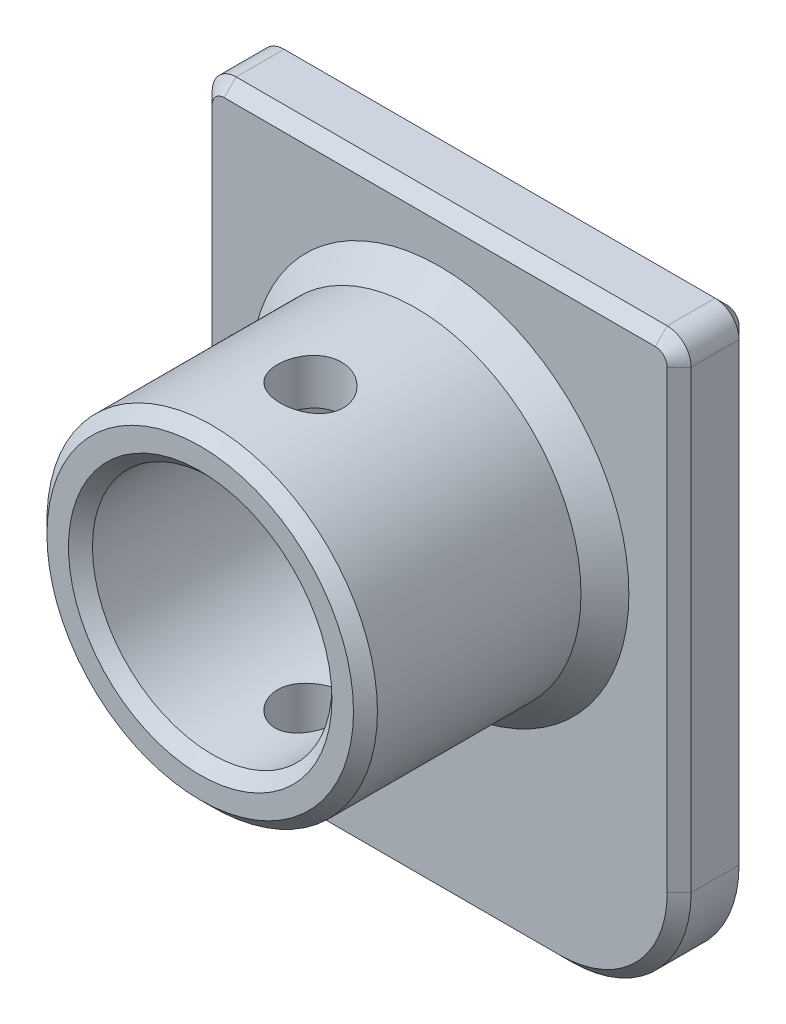
SolidWorks part; units mm, degrees
ref_plane "Front Plane" through (0, 0, 0) normal (0, 0, 1) x (1, 0, 0)
ref_plane "Top Plane" through (0, 0, 0) normal (0, 1, 0) x (1, 0, 0)
ref_plane "Right Plane" through (0, 0, 0) normal (1, 0, 0) x (0, 0, -1)
sketch "Sketch2" plane through (0, 0, 0) normal (0, 0, 1) x (1, 0, 0)
  line L0 (111.7654, 138.8608) -> (111.7654, 113.8608) construction
  line L1 (102.7654, 138.8608) -> (120.7654, 138.8608)
  line L2 (101.7654, 137.8608) -> (101.7654, 118.8608)
  line L3 (106.7654, 113.8608) -> (116.7654, 113.8608)
  line L4 (121.7654, 137.8608) -> (121.7654, 118.8608)
  line L5 (121.7654, 128.3608) -> (101.7654, 128.3608) construction
  line L6 (101.7654, 128.8608) -> (121.7654, 128.8608) construction
  circle A0 centre (111.7654, 128.8608) radius 5
  circle A1 centre (111.7654, 128.8608) radius 6.9
  arc A2 (116.7654, 113.8608) -> (121.7654, 118.8608) centre (116.7654, 118.8608) ccw
  arc A3 (101.7654, 118.8608) -> (106.7654, 113.8608) centre (106.7654, 118.8608) ccw
  arc A4 (120.7654, 138.8608) -> (121.7654, 137.8608) centre (120.7654, 137.8608) cw
  arc A5 (102.7654, 138.8608) -> (101.7654, 137.8608) centre (102.7654, 137.8608) ccw
  point P15 (121.7654, 113.8608)
  point P18 (101.7654, 113.8608)
  point P21 (121.7654, 138.8608)
  dimension "D4" = 10
  dimension "D5" = 13.8
  dimension "D6" = 5
  dimension "D7" = 1
  dimension "D1" = 25
  dimension "D2" = 20
  dimension "D3" = 10
extrude "Boss-Extrude1" add sketch "Sketch2" along normal blind 3 contours L1 A5 L2 A3 L3 A2 L4 A4 A1
sketch "Sketch3" plane through (0, 0, 0) normal (0, 0, 1) x (1, 0, 0)
  circle A0 centre (111.7654, 128.8608) radius 5
  circle A1 centre (111.7654, 128.8608) radius 6.9
extrude "Boss-Extrude2" add sketch "Sketch3" along normal blind 13
chamfer "Chamfer1" distance 0.5 angle 45 19 edges at (121.4725, 138.5679, 3) (121.7654, 128.3608, 3) (120.301, 115.3253, 3) (111.7654, 113.8608, 3) (103.2299, 115.3253, 3) (101.7654, 128.3608, 3) (102.0583, 138.5679, 3) (111.7654, 138.8608, 3) (116.7654, 128.8608, 0) (102.0583, 138.5679, 0) (101.7654, 128.3608, 0) (103.2299, 115.3253, 0) (111.7654, 113.8608, 0) (120.301, 115.3253, 0) (121.7654, 128.3608, 0) (121.4725, 138.5679, 0) (111.7654, 138.8608, 0) (116.7654, 128.8608, 13) (118.6654, 128.8608, 13)
chamfer "Chamfer2" distance 1 angle 45 1 edges at (118.6654, 128.8608, 3)
sketch "Sketch4" plane through (0, 138.8608, 0) normal (0, 1, 0) x (1, 0, 0)
  line L0 (105.3654, -13) -> (118.1654, -13) construction
  circle A0 centre (112.2442, -8.875) radius 1.375
  dimension "D1" = 4.125
  dimension "D2" = 2.75
extrude "Cut-Extrude1" cut sketch "Sketch4" against normal blind 20
